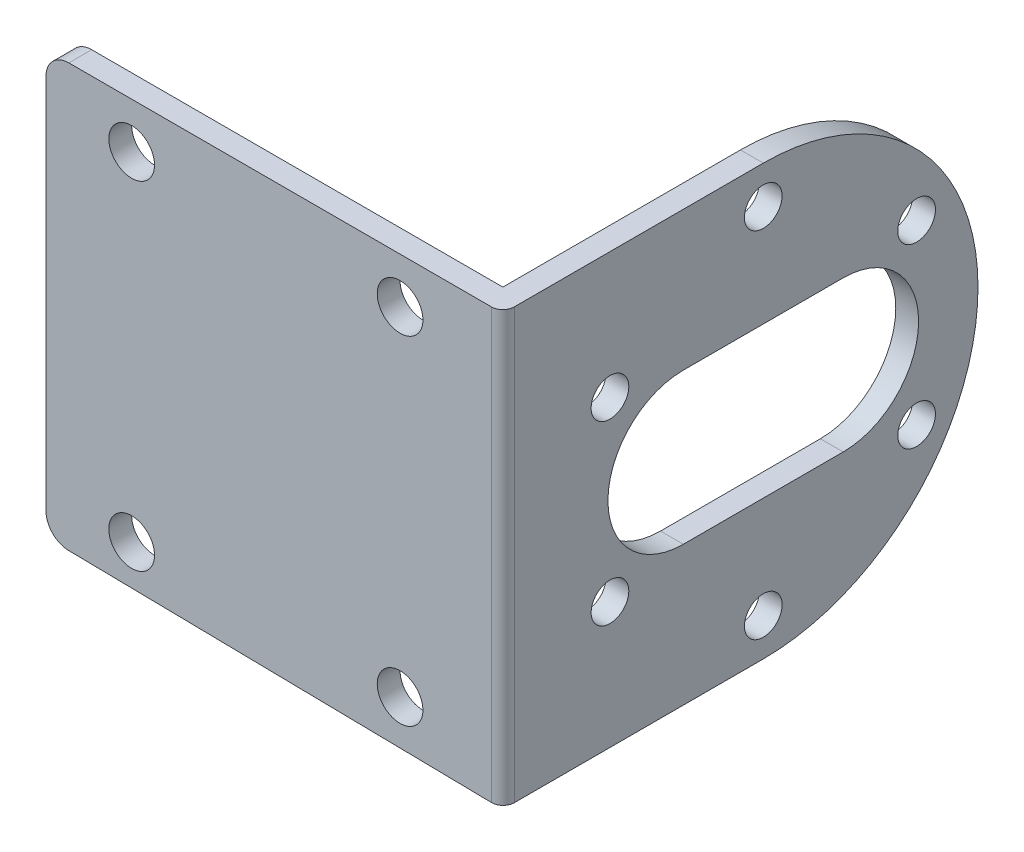
SolidWorks part; units mm, degrees
ref_plane "Alzado" through (0, 0, 0) normal (0, 0, 1) x (1, 0, 0)
ref_plane "Planta" through (0, 0, 0) normal (0, 1, 0) x (1, 0, 0)
ref_plane "Vista lateral" through (0, 0, 0) normal (1, 0, 0) x (0, 0, -1)
sketch "Croquis1" plane through (0, 0, 0) normal (1, 0, 0) x (0, 0, -1)
  line L0 (0, 0) -> (63.0829, 0) construction
  line L1 (0, 0) -> (13.4234, 7.75) construction
  line L2 (0, 0) -> (0, 18.8) construction
  line L3 (0, 18.8) -> (-20.8, 18.8)
  line L4 (0, -18.8) -> (-20.8, -18.8)
  line L5 (-20.8, -18.8) -> (-20.8, 18.8)
  line L6 (-7, 0) -> (7, 0) construction
  line L7 (-7, 6.6) -> (7, 6.6)
  line L8 (-7, -6.6) -> (7, -6.6)
  circle A0 centre (13.4234, 7.75) radius 1.65
  circle A1 centre (13.4234, -7.75) radius 1.65
  circle A2 centre (0, -15.5) radius 1.65
  circle A3 centre (-13.4234, -7.75) radius 1.65
  circle A4 centre (-13.4234, 7.75) radius 1.65
  circle A5 centre (0, 15.5) radius 1.65
  arc A6 (0, 18.8) -> (0, -18.8) centre (0, 0) cw
  arc A7 (-7, 6.6) -> (-7, -6.6) centre (-7, 0) ccw
  arc A8 (7, -6.6) -> (7, 6.6) centre (7, 0) ccw
  point P21 (0, 0)
  dimension "D3" = 3.3
  dimension "D1" = 30
  dimension "D2" = 15.5
  dimension "D4" = 18.8
  dimension "D6" = 20.8
  dimension "D7" = 14
  dimension "D5" = 6
extrude "Saliente-Extruir1" add sketch "Croquis1" along normal blind 2
sketch "Croquis2" plane through (0, 0, 20.8) normal (0, 0, 1) x (1, 0, 0)
  line L0 (2, 18.8) -> (-38, 18.8)
  line L1 (2, 18.8) -> (2, -18.8)
  line L2 (2, -18.8) -> (-38, -18.1506)
  line L3 (-38, -18.1506) -> (-38, 18.8)
  dimension "D1" = 40
extrude "Saliente-Extruir2" add sketch "Croquis2" along normal blind 2
fillet "Redondeo1" radius 1 1 edges at (2, 0, 22.8)
fillet "Redondeo2" radius 2 2 edges at (-38, 18.8, 21.8) (-38, -18.1506, 21.8)
sketch "Croquis3" plane through (0, 0, 22.8) normal (0, 0, 1) x (1, 0, 0)
  line L0 (2, 14.8) -> (-7, 14.8) construction
  line L1 (2, 18.8) -> (2, -18.8) construction
  line L2 (-7, 14.8) -> (-7, 18.8) construction
  line L3 (1, 18.8) -> (-36, 18.8) construction
  line L4 (1, 0.0081) -> (-30.3834, 0.0081) construction
  line L5 (1, -18.7838) -> (1, 18.8) construction
  line L6 (-7, 14.8) -> (-30.5, 14.8) construction
  line L7 (-30.5, 14.8) -> (-30.5, -14.7838) construction
  circle A0 centre (-7, 14.8) radius 2
  circle A1 centre (-7, -14.7838) radius 2
  circle A2 centre (-30.5, 14.8) radius 2
  circle A3 centre (-30.5, -14.7838) radius 2
  dimension "D3" = 4
  dimension "D5" = 4
  dimension "D6" = 4
  dimension "D1" = 9
  dimension "D2" = 4
  dimension "D4" = 23.5
extrude "Cortar-Extruir1" cut sketch "Croquis3" against normal through all
